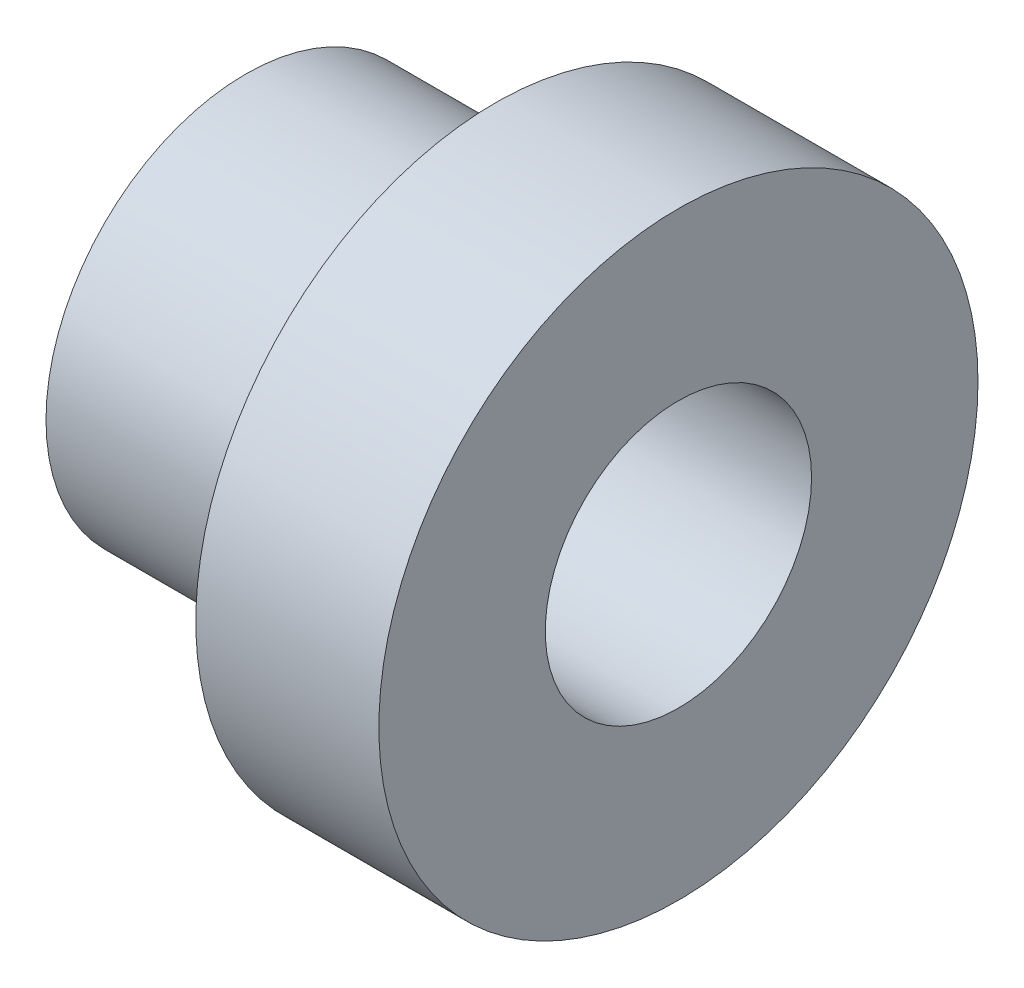
SolidWorks part; units mm, degrees
ref_plane "前视基准面" through (0, 0, 0) normal (0, 0, 1) x (1, 0, 0)
ref_plane "上视基准面" through (0, 0, 0) normal (0, 1, 0) x (1, 0, 0)
ref_plane "右视基准面" through (0, 0, 0) normal (1, 0, 0) x (0, 0, -1)
sketch "草图1" plane through (0, 0, 0) normal (0, 0, 1) x (1, 0, 0)
  line L0 (0, 0) -> (-55.3008, 0) construction
  line L1 (0, 4) -> (0, 9)
  line L2 (0, 9) -> (-5.5, 9)
  line L3 (-5.5, 9) -> (-5.5, 6)
  line L4 (-5.5, 6) -> (-13, 6)
  line L5 (-13, 6) -> (-13, 4)
  line L6 (-13, 4) -> (0, 4)
  dimension "D1" = 9
  dimension "D2" = 6
  dimension "D3" = 5.5
  dimension "D4" = 13
  dimension "D5" = 4
revolve "旋转1" add sketch "草图1" angle 360 about L0
